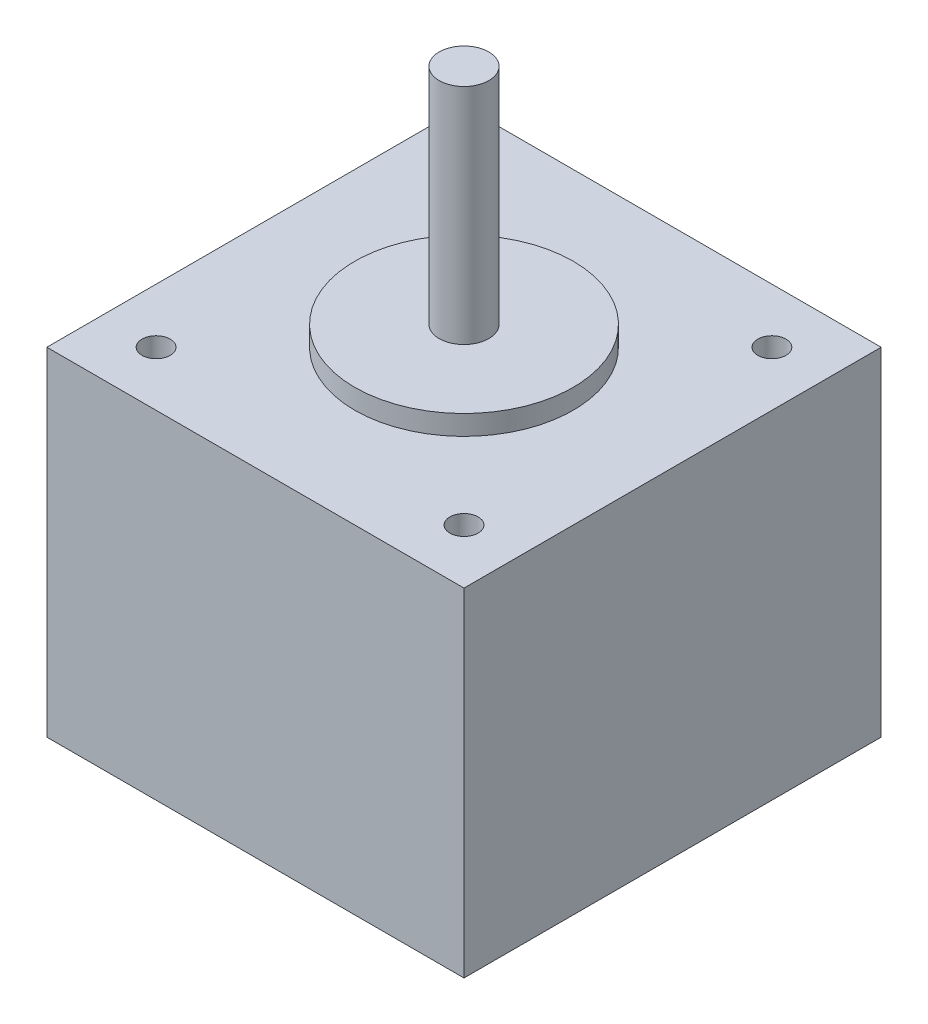
SolidWorks part; units mm, degrees
ref_plane "Front Plane" through (0, 0, 0) normal (0, 0, 1) x (1, 0, 0)
ref_plane "Top Plane" through (0, 0, 0) normal (0, 1, 0) x (1, 0, 0)
ref_plane "Right Plane" through (0, 0, 0) normal (1, 0, 0) x (0, 0, -1)
sketch "Sketch1" plane through (0, 0, 0) normal (0, 1, 0) x (1, 0, 0)
  line L1 (-21, -21) -> (21, -21)
  line L2 (-21, -21) -> (-21, 21)
  line L3 (-21, 21) -> (21, 21)
  line L4 (21, -21) -> (21, 21)
  line L5 (-21, -21) -> (21, 21) construction
  line L6 (-21, 21) -> (21, -21) construction
  point P0 (0, 0)
  dimension "D1" = 42
  dimension "D2" = 42
extrude "Boss-Extrude1" add sketch "Sketch1" along normal blind 34
sketch "Sketch2" plane through (0, 34, 0) normal (0, 1, 0) x (1, 0, 0)
  circle A0 centre (0, 0) radius 11
  dimension "D1" = 22
extrude "Boss-Extrude2" add sketch "Sketch2" along normal blind 2
sketch "Sketch3" plane through (0, 36, 0) normal (0, 1, 0) x (1, 0, 0)
  circle A0 centre (0, 0) radius 2.5
  dimension "D1" = 5
extrude "Boss-Extrude3" add sketch "Sketch3" along normal blind 22.5
sketch "Sketch4" plane through (0, 34, 0) normal (0, 1, 0) x (1, 0, 0)
  circle A0 centre (-15.5, 15.5) radius 1.42
  circle A1 centre (15.5, 15.5) radius 1.42
  circle A2 centre (15.5, -15.5) radius 1.42
  circle A3 centre (-15.5, -15.5) radius 1.42
  dimension "D1" = 2.84
  dimension "D2" = 15.5
  dimension "D3" = 15.5
  dimension "D4" = 2
  dimension "D5" = 2
extrude "Cut-Extrude1" cut sketch "Sketch4" against normal blind 5
